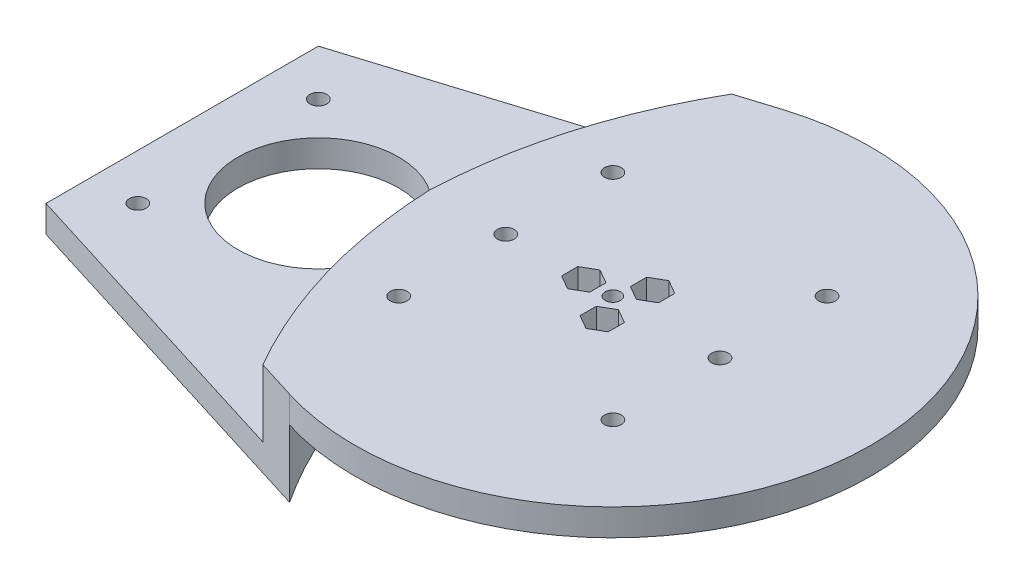
SolidWorks part; units mm, degrees
ref_plane "Front Plane" through (0, 0, 0) normal (0, 0, 1) x (1, 0, 0)
ref_plane "Top Plane" through (0, 0, 0) normal (0, 1, 0) x (1, 0, 0)
ref_plane "Right Plane" through (0, 0, 0) normal (1, 0, 0) x (0, 0, -1)
sketch "Sketch1" plane through (0, 0, 0) normal (0, 1, 0) x (1, 0, 0)
  line L0 (-112.6, -35.6) -> (-112.6, 35.6)
  line L5 (-112.6, 35.6) -> (-20.0902, 64.4409)
  line L6 (-112.6, -35.6) -> (-20.0902, -64.4409)
  arc A0 (-20.0902, -64.4409) -> (-20.0902, 64.4409) centre (0, 0) ccw
  circle A1 centre (-77, 0) radius 21
  circle A6 centre (-100.6, 23.6) radius 2.2
  circle A7 centre (-100.6, -23.6) radius 2.2
  circle A8 centre (-53.4, -23.6) radius 2.2
  circle A9 centre (-53.4, 23.6) radius 2.2
  dimension "D1" = 135
  dimension "D3" = 42
  dimension "D6" = 47.2
  dimension "D10" = 4.4
  dimension "D11" = 4.4
  dimension "D12" = 4.4
  dimension "D13" = 4.4
  dimension "D2" = 77
  dimension "D4" = 47.2
  dimension "D5" = 47.2
  dimension "D7" = 47.2
  dimension "D8" = 23.6
  dimension "D9" = 23.6
  dimension "D14" = 23.6
  dimension "D15" = 23.6
  dimension "D16" = 12
  dimension "D17" = 12
  dimension "D18" = 12
extrude "Boss-Extrude1" add sketch "Sketch1" along normal blind 7
sketch "Sketch3" plane through (0, 0, 0) normal (0, -1, 0) x (1, 0, 0)
  circle A0 centre (0, 0) radius 11.25
  circle A1 centre (0, 0) radius 2
  dimension "D1" = 22.5
  dimension "D2" = 4
extrude "Boss-Extrude2" add sketch "Sketch3" along normal blind 14
sketch "Sketch4" plane through (0, -14, 0) normal (0, -1, 0) x (1, 0, 0)
  circle A0 centre (0, 0) radius 11.25
  circle A1 centre (0, 0) radius 9.9
  dimension "D1" = 19.8
extrude "Cut-Extrude1" cut sketch "Sketch4" against normal blind 1.5
sketch "Sketch5" plane through (0, -14, 0) normal (0, -1, 0) x (1, 0, 0)
  circle A0 centre (-7.6, 0) radius 2.2
  circle A1 centre (3.8, 6.5818) radius 2.2
  circle A2 centre (3.8, -6.5818) radius 2.2
  point P9 (0, 0)
  dimension "D1" = 4.4
  dimension "D2" = 7.6
  dimension "D3" = 3
extrude "Cut-Extrude2" cut sketch "Sketch5" against normal through all
sketch "Sketch6" plane through (0, 7, 0) normal (0, 1, 0) x (1, 0, 0)
  line L0 (3.8, 2.3383) -> (7.475, 4.46)
  line L1 (-7.6, -4.2435) -> (-3.925, -2.1218)
  line L2 (-3.925, -2.1218) -> (-3.925, 2.1218)
  line L3 (-3.925, 2.1218) -> (-7.6, 4.2435)
  line L4 (-7.6, 4.2435) -> (-11.275, 2.1218)
  line L5 (-11.275, 2.1218) -> (-11.275, -2.1218)
  line L6 (-11.275, -2.1218) -> (-7.6, -4.2435)
  line L7 (7.475, 4.46) -> (7.475, 8.7036)
  line L8 (7.475, 8.7036) -> (3.8, 10.8253)
  line L9 (3.8, 10.8253) -> (0.125, 8.7036)
  line L10 (0.125, 8.7036) -> (0.125, 4.46)
  line L11 (0.125, 4.46) -> (3.8, 2.3383)
  line L12 (0.125, -4.46) -> (0.125, -8.7036)
  line L13 (0.125, -8.7036) -> (3.8, -10.8253)
  line L14 (3.8, -10.8253) -> (7.475, -8.7036)
  line L15 (7.475, -8.7036) -> (7.475, -4.46)
  line L16 (7.475, -4.46) -> (3.8, -2.3383)
  line L17 (3.8, -2.3383) -> (0.125, -4.46)
  circle A3 centre (-7.6, 0) radius 3.675 construction
  point P9 (0, 0)
  point P26 (0, 0)
  dimension "D1" = 7.35
  dimension "D2" = 3
extrude "Cut-Extrude3" cut sketch "Sketch6" against normal blind 6.5
sketch "Sketch7" plane through (0, 0, 0) normal (0, -1, 0) x (1, 0, 0)
  circle A0 centre (0, 0) radius 2
extrude "Cut-Extrude4" cut sketch "Sketch7" against normal blind 10
sketch "Sketch8" plane through (0, 7, 0) normal (0, 1, 0) x (1, 0, 0)
  circle A0 centre (-28, 0) radius 2.2
  circle A1 centre (28, 0) radius 2.2
  circle A2 centre (28, 28) radius 2.2
  circle A3 centre (-28, 28) radius 2.2
  circle A4 centre (-28, -28) radius 2.2
  circle A5 centre (28, -28) radius 2.2
  dimension "D1" = 4.4
  dimension "D2" = 28
  dimension "D3" = 2
  dimension "D4" = 2
  dimension "D5" = 2
extrude "Cut-Extrude5" cut sketch "Sketch8" against normal through all
sketch "Sketch9" plane through (0, 0, 0) normal (0, -1, 0) x (1, 0, 0)
  circle A0 centre (-28, 28) radius 4.15
  circle A1 centre (28, 28) radius 4.15
  circle A2 centre (-28, 0) radius 4.15
  circle A3 centre (28, 0) radius 4.15
  circle A4 centre (-28, -28) radius 4.15
  circle A5 centre (28, -28) radius 4.15
  dimension "D1" = 8.3
  dimension "D2" = 8.3
  dimension "D3" = 3
extrude "Cut-Extrude6" cut sketch "Sketch9" against normal blind 3
sketch "Sketch10" plane through (0, 0, 0) normal (0, -1, 0) x (1, 0, 0)
  line L0 (-35.3321, 0) -> (-16.4332, 0) construction
  line L1 (-20.0902, -64.4409) -> (-112.6, -35.6) construction
  line L2 (-112.6, -35.6) -> (-112.6, 35.6) construction
  line L3 (-112.6, 35.6) -> (-20.0902, 64.4409) construction
  line L4 (-20.0902, -64.4409) -> (-112.6, -35.6)
  line L5 (-112.6, -35.6) -> (-112.6, 35.6)
  line L6 (-112.6, 35.6) -> (-20.0902, 64.4409)
  circle A0 centre (-77, 0) radius 21 construction
  circle A1 centre (-100.6, 23.6) radius 2.2 construction
  circle A2 centre (-53.4, 23.6) radius 2.2 construction
  circle A3 centre (-53.4, -23.6) radius 2.2 construction
  circle A4 centre (-100.6, -23.6) radius 2.2 construction
  circle A5 centre (-77, 0) radius 21
  circle A6 centre (-100.6, 23.6) radius 2.2
  circle A7 centre (-53.4, 23.6) radius 2.2
  circle A8 centre (-53.4, -23.6) radius 2.2
  circle A9 centre (-100.6, -23.6) radius 2.2
  spline S0 degree 2 poles (-20.0902, 64.4409) (-39.3183, 35.0158) (-40.9879, 0) knots 0 0 0 1 1 1
  spline S1 degree 2 poles (-20.0902, -64.4409) (-39.3183, -35.0158) (-40.9879, 0) knots 0 0 0 1 1 1
extrude "Boss-Extrude3" add sketch "Sketch10" along normal blind 17.5
sketch "Sketch11" plane through (0, 7, 0) normal (0, 1, 0) x (1, 0, 0)
  line L0 (-25.95, 68.2701) -> (-139.3216, 44.0187)
  line L1 (-139.3216, 44.0187) -> (-144.3139, -55.4175)
  line L2 (-144.3139, -55.4175) -> (-25.95, -68.2701)
  spline S2 degree 3 poles (-25.95, 68.2701) (-26.7922, 66.9813) (-28.4398, 64.3702) (-31.5336, 59.0974) (-35.0461, 52.3743) (-38.6812, 44.111) (-41.7347, 35.6544) (-44.2032, 27.0112) (-46.0856, 18.1886) (-47.1657, 10.6893) (-47.737, 4.6116) (-47.9258, 1.5354) (-47.9954, 0) knots 0.498906 0.498906 0.498906 0.498906 0.499041 0.499175 0.499445 0.499714 0.499984 0.500253 0.500523 0.500792 0.500927 0.501062 0.501062 0.501062 0.501062
  spline S3 degree 3 poles (-47.9954, 0) (-47.9258, -1.5354) (-47.737, -4.6116) (-47.1657, -10.6893) (-46.0856, -18.1886) (-44.2032, -27.0112) (-41.7347, -35.6544) (-38.6812, -44.111) (-35.0461, -52.3743) (-31.5336, -59.0974) (-28.4398, -64.3702) (-26.7922, -66.9813) (-25.95, -68.2701) knots 0.498938 0.498938 0.498938 0.498938 0.499073 0.499208 0.499477 0.499747 0.500016 0.500286 0.500555 0.500825 0.500959 0.501094 0.501094 0.501094 0.501094
extrude "Cut-Extrude7" cut sketch "Sketch11" against normal blind 17.5
